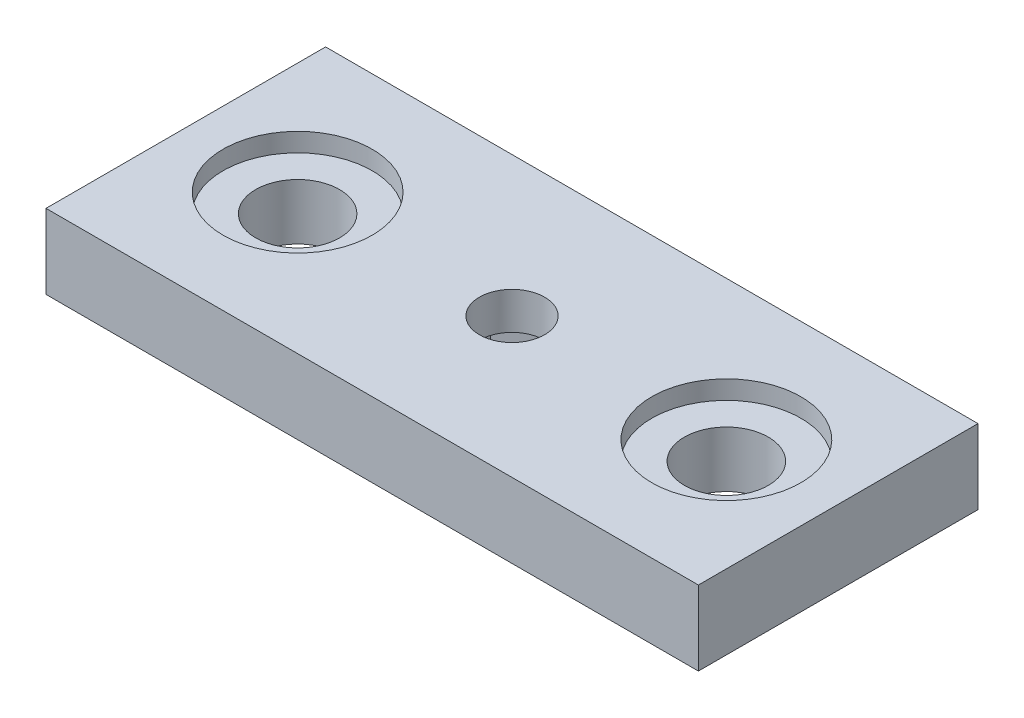
SolidWorks part; units mm, degrees
ref_plane "前基準面" through (0, 0, 0) normal (0, 0, 1) x (1, 0, 0)
ref_plane "上基準面" through (0, 0, 0) normal (0, 1, 0) x (1, 0, 0)
ref_plane "右基準面" through (0, 0, 0) normal (1, 0, 0) x (0, 0, -1)
sketch "草圖1" plane through (0, 0, 0) normal (0, 1, 0) x (1, 0, 0)
  line L1 (0, 0) -> (35, 0)
  line L2 (0, 0) -> (0, 15)
  line L3 (0, 15) -> (35, 15)
  line L4 (35, 0) -> (35, 15)
  dimension "D1" = 35
  dimension "D2" = 15
extrude "填料-伸長1" add sketch "草圖1" along normal blind 4
hole_wizard "Ø3.5 (3.5) 直徑孔1" positions "草圖3" profile "草圖2" hole size "Ø3.5" standard "Ansi Metric" end condition through all
sketch "草圖3" plane through (0, 4, 0) normal (0, 1, 0) x (1, 0, 0)
  line L0 (0, 7.5) -> (35, 7.5)
  line L1 (0, 15) -> (0, 0) construction
  line L2 (35, 0) -> (35, 15) construction
  point P0 (17.5, 7.5)
sketch "草圖2" plane through (17.5, 4, -7.5) normal (1, 0, 0) x (0, 0, 1)
  line L0 (0, 0) -> (0, 4)
  line L1 (0, 4) -> (1.75, 4)
  line L2 (1.75, 4) -> (1.75, 0)
  line L5 (1.75, 0) -> (0, 0)
  line L11 (0, -6.35) -> (0, 107.95) construction
  dimension "貫穿孔直徑" = 3.5
  dimension "貫穿孔深度" = 4
hole_wizard "鑽孔1" positions "草圖7" profile "草圖6" legacy end condition through all
sketch "草圖7" plane through (0, 4, 0) normal (0, 1, 0) x (1, 0, 0)
  line L0 (0, 7.5) -> (35, 7.5)
  line L1 (0, 15) -> (0, 0) construction
  line L2 (35, 0) -> (35, 15) construction
  point P0 (6, 7.5)
  point P2 (29, 7.5)
  dimension "D1" = 6
  dimension "D2" = 6
sketch "草圖6" plane through (6, 4, -7.5) normal (1, 0, 0) x (0, 0, 1)
  line L0 (0, 0) -> (0, 4)
  line L1 (0, 4) -> (2.25, 4)
  line L2 (2.25, 4) -> (2.25, 1)
  line L3 (2.25, 1) -> (4, 1)
  line L4 (4, 1) -> (4, 0)
  line L5 (4, 0) -> (0, 0)
  line L6 (0, -6.13) -> (0, 109.2824) construction
  line L7 (-2.25, 1) -> (-4, 1) construction
  line L8 (0, 4) -> (-2.25, 4) construction
  dimension "直徑" = 4.5
  dimension "深度" = 4
  dimension "沈頭孔直徑" = 8
  dimension "沈頭孔深度" = 1
  dimension "沈頭孔角度" = 180
sketch "草圖8" plane through (0, 0, 0) normal (0, -1, 0) x (1, 0, 0)
  line L1 (17.5, -10.6754) -> (20.25, -9.0877)
  line L2 (20.25, -9.0877) -> (20.25, -5.9123)
  line L3 (20.25, -5.9123) -> (17.5, -4.3246)
  line L4 (17.5, -4.3246) -> (14.75, -5.9123)
  line L5 (14.75, -5.9123) -> (14.75, -9.0877)
  line L6 (14.75, -9.0877) -> (17.5, -10.6754)
  circle A0 centre (17.5, -7.5) radius 2.75 construction
  dimension "D1" = 5.5
extrude "除料-伸長1" cut sketch "草圖8" against normal blind 2
